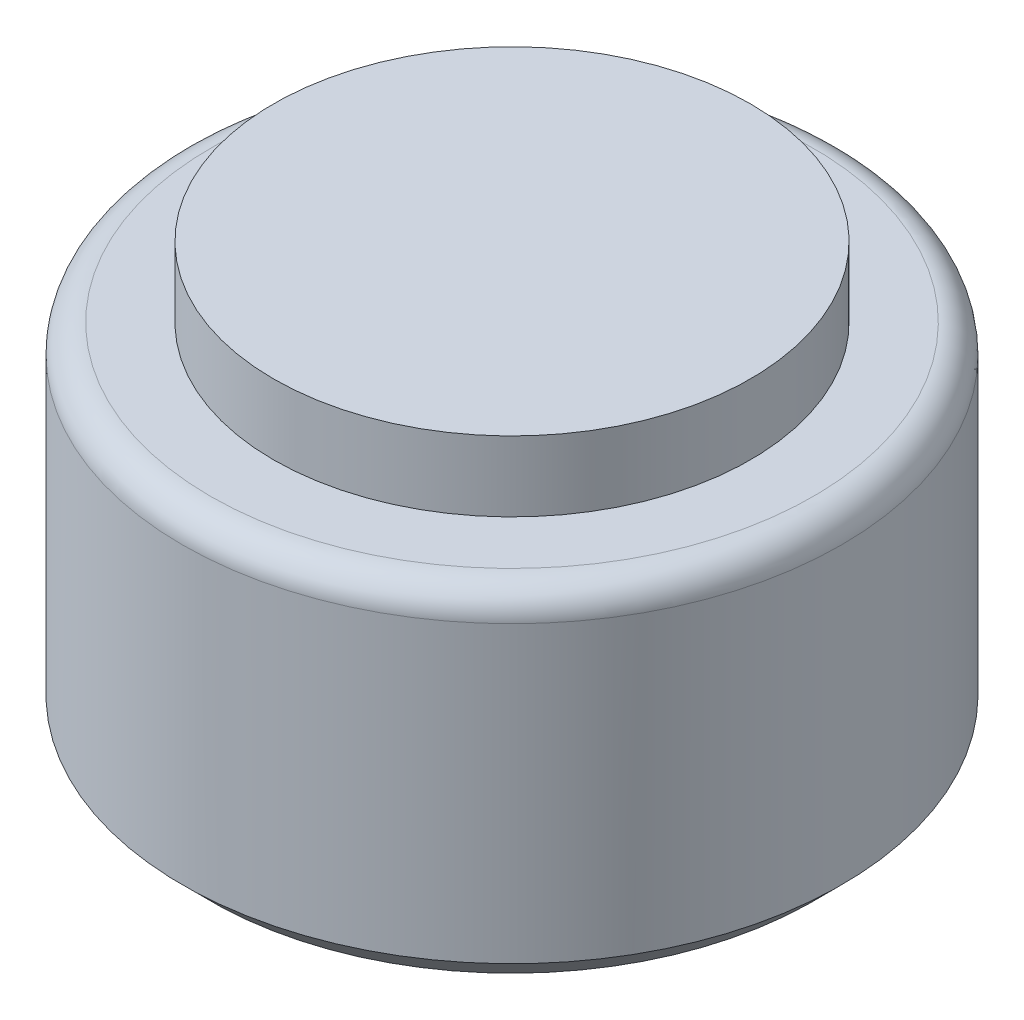
SolidWorks part; units mm, degrees
ref_plane "Front" through (0, 0, 0) normal (0, 0, 1) x (1, 0, 0)
ref_plane "Top" through (0, 0, 0) normal (0, 1, 0) x (1, 0, 0)
ref_plane "Right" through (0, 0, 0) normal (1, 0, 0) x (0, 0, -1)
sketch "草图1" plane through (0, 0, 0) normal (0, 0, 1) x (1, 0, 0)
  line L0 (0, 0) -> (85, 0)
  line L1 (85, 0) -> (85, -25)
  line L2 (85, -25) -> (117.5, -25)
  line L3 (117.5, -25) -> (117.5, -150)
  line L4 (117.5, -150) -> (67.5, -150)
  line L5 (67.5, -150) -> (67.5, -110)
  line L6 (67.5, -110) -> (0, -110)
  line L7 (0, -110) -> (0, 0)
  line L8 (0, 0) -> (0, 41.4616) construction
  point P9 (33.75, -110)
  dimension "D1" = 170
  dimension "D2" = 25
  dimension "D3" = 235
  dimension "D4" = 150
  dimension "D5" = 40
  dimension "D6" = 135
revolve "旋转1" add sketch "草图1" angle 360 about L8
hole_wizard "M16 螺纹孔1" positions "草图2" profile "草图3" tap size "M16" standard "ISO"
sketch "草图2" plane through (0, -110, 0) normal (0, -1, 0) x (-1, 0, 0)
  point P0 (0, 0)
sketch "草图3" plane through (0, -110, 0) normal (1, 0, 0) x (0, 0, -1)
  line L0 (0, 0) -> (0, 42.206)
  line L1 (0, 42.206) -> (7, 38)
  line L2 (7, 38) -> (7, 0)
  line L5 (7, 0) -> (0, 0)
  line L10 (0, 42.206) -> (-7, 38) construction
  line L11 (0, -6.35) -> (0, 107.95) construction
  dimension "螺纹孔钻头直径" = 14
  dimension "螺纹孔钻头深度" = 38
  dimension "导头角度" = 118
cosmetic thread "孔螺蚊线1" parameters "D1"=32, "D2"=16
chamfer "倒角1" distance 10 angle 45 1 edges at (0, -150, -117.5)
fillet "圆角1" radius 10 1 edges at (0, -25, -117.5)
